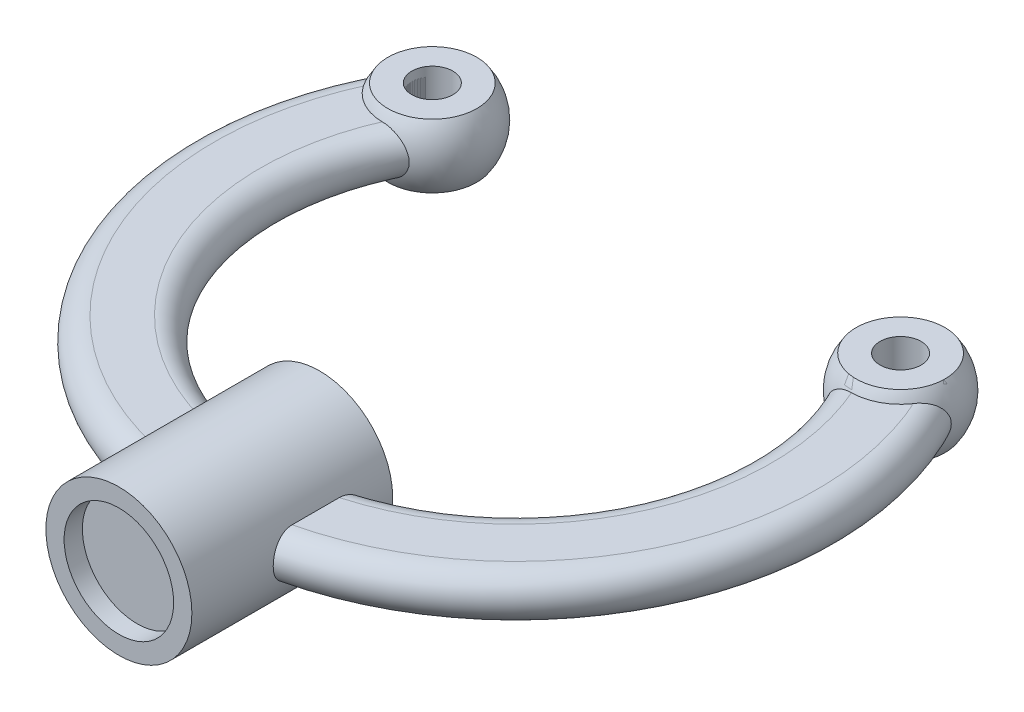
SolidWorks part; units mm, degrees
material "1060 Alloy"
ref_plane "Front Plane" through (0, 0, 0) normal (0, 0, 1) x (1, 0, 0)
ref_plane "Top Plane" through (0, 0, 0) normal (0, 1, 0) x (1, 0, 0)
ref_plane "Right Plane" through (0, 0, 0) normal (1, 0, 0) x (0, 0, -1)
sketch "Sketch1" plane through (0, 0, 0) normal (1, 0, 0) x (0, 0, -1)
  line L0 (0, 0) -> (10, 0) construction
  line L3 (0, 0) -> (10, 0) construction
  line L4 (0, 5) -> (10, 5)
  line L5 (0, -5) -> (10, -5)
  line L6 (66, 16.0008) -> (66, -15.6966) construction
  arc A0 (0, 5) -> (0, -5) centre (0, 0) ccw
  arc A1 (10, -5) -> (10, 5) centre (10, 0) ccw
  point P2 (5, 0)
  dimension "D3" = 5
  dimension "D1" = 10
  dimension "D2" = 61
revolve "Revolve1" add sketch "Sketch1" angle 360 about L6
sketch "Sketch2" plane through (0, 0, 0) normal (0, 1, 0) x (1, 0, 0)
  line L0 (-80.8422, -21) -> (72.9635, -21) construction
  line L1 (-118.9396, 23) -> (0, 23) construction
  line L2 (0, 66) -> (-51.303, 99) construction
  line L3 (-51.303, 99) -> (51.303, 99) construction
  line L4 (-51.303, 99) -> (-80.0007, 117.4594) construction
  line L5 (-61.3954, 105.4918) -> (-41.2106, 92.5082)
  circle A0 centre (0, 66) radius 61
  arc A1 (-61.3954, 105.4918) -> (-41.2106, 92.5082) centre (-51.303, 99) ccw
  dimension "D1" = 122
  dimension "D5" = 12
  dimension "D2" = 44
  dimension "D3" = 87
  dimension "D4" = 120
revolve "Revolve2" add sketch "Sketch2" angle 360 about L4
sketch "Sketch9" plane through (0, 0, 0) normal (0, 1, 0) x (1, 0, 0)
  line L0 (-98.865, 99) -> (51.303, 99) construction
  line L1 (-93.987, -21) -> (64.4876, -21) construction
  line L2 (0, 66) -> (-101.7905, 66) construction
  line L3 (51.303, 99) -> (69.6523, 99) construction
  line L4 (39.303, 99) -> (63.303, 99)
  circle A0 centre (0, 66) radius 61 construction
  arc A1 (63.303, 99) -> (39.303, 99) centre (51.303, 99) ccw
  dimension "D3" = 122
  dimension "D4" = 24
  dimension "D1" = 120
  dimension "D2" = 87
revolve "Revolve4" add sketch "Sketch9" angle 360 about L4
ref_plane "top cut plane" through (0, 7, 0) normal (0, 1, 0) x (1, 0, 0)
sketch "Sketch7" plane through (0, 7, 0) normal (0, 1, 0) x (1, 0, 0)
  line L1 (-71, 66) -> (67.6672, 66)
  line L2 (-71, 66) -> (-71, 128.2523)
  line L3 (-71, 128.2523) -> (67.6672, 128.2523)
  line L4 (67.6672, 66) -> (67.6672, 128.2523)
  circle A0 centre (0, 66) radius 71 construction
ref_plane "bottom cut plane" through (0, -7, 0) normal (0, -1, 0) x (-1, 0, 0)
extrude "Cut-Extrude4" cut sketch "Sketch7" along normal through all
sketch "Sketch8" plane through (0, -7, 0) normal (0, -1, 0) x (-1, 0, 0)
  line L1 (-70.2285, 123.2279) -> (80.5904, 123.2279)
  line L2 (-70.2285, 123.2279) -> (-70.2285, 66.6955)
  line L3 (-70.2285, 66.6955) -> (80.5904, 66.6955)
  line L4 (80.5904, 123.2279) -> (80.5904, 66.6955)
extrude "Cut-Extrude5" cut sketch "Sketch8" along normal through all
sketch "Sketch12" plane through (0, 7, 0) normal (0, 1, 0) x (1, 0, 0)
  circle A0 centre (-51.303, 99) radius 4.5
  circle A1 centre (51.303, 99) radius 4.5
  dimension "D1" = 9
  dimension "D2" = 9
extrude "Cut-Extrude6" cut sketch "Sketch12" against normal through all
surface "Surface-Offset3" parameters "D1"=0
sketch "Sketch13" plane through (0, 0, 0) normal (0, 1, 0) x (1, 0, 0)
  line L0 (0, 66) -> (-51.303, 99)
  line L1 (0, 66) -> (51.303, 99)
  line L2 (-51.303, 99) -> (-118.5857, 142.2787)
  line L3 (51.303, 99) -> (118.5857, 142.2787)
  line L4 (-118.5857, 142.2787) -> (118.5857, 142.2787)
  dimension "D1" = 80
  dimension "D2" = 80
extrude "Cut-Extrude7" cut sketch "Sketch13" against normal through all and the other way through all
sketch "Sketch14" plane through (0, 0, 0) normal (0, 0, 1) x (1, 0, 0)
  circle A0 centre (0, 0) radius 16
  dimension "D1" = 32
extrude "Boss-Extrude2" add sketch "Sketch14" along normal blind 21 and the other way blind 23
sketch "Sketch16" plane through (0, 0, 21) normal (0, 0, 1) x (1, 0, 0)
  circle A0 centre (0, 0) radius 12
  dimension "D1" = 24
extrude "Cut-Extrude8" cut sketch "Sketch16" against normal through all
sketch "Sketch17" plane through (0, 0, 0) normal (0, 1, 0) x (1, 0, 0)
  line L0 (-15.5623, -21) -> (-75.3305, -21) construction
  line L1 (-16, -21) -> (16, -21) construction
  line L2 (0, 0) -> (0, -31.7246) construction
  line L4 (-14, -15) -> (0, -15)
  line L5 (-14, -15) -> (-14, -17)
  line L6 (-14, -17) -> (0, -17)
  line L7 (0, -15) -> (0, -17)
  dimension "D1" = 14
  dimension "D2" = 2
  dimension "D3" = 4
  dimension "D4" = 0
revolve "Revolve5" add sketch "Sketch17" angle 360 about L2
